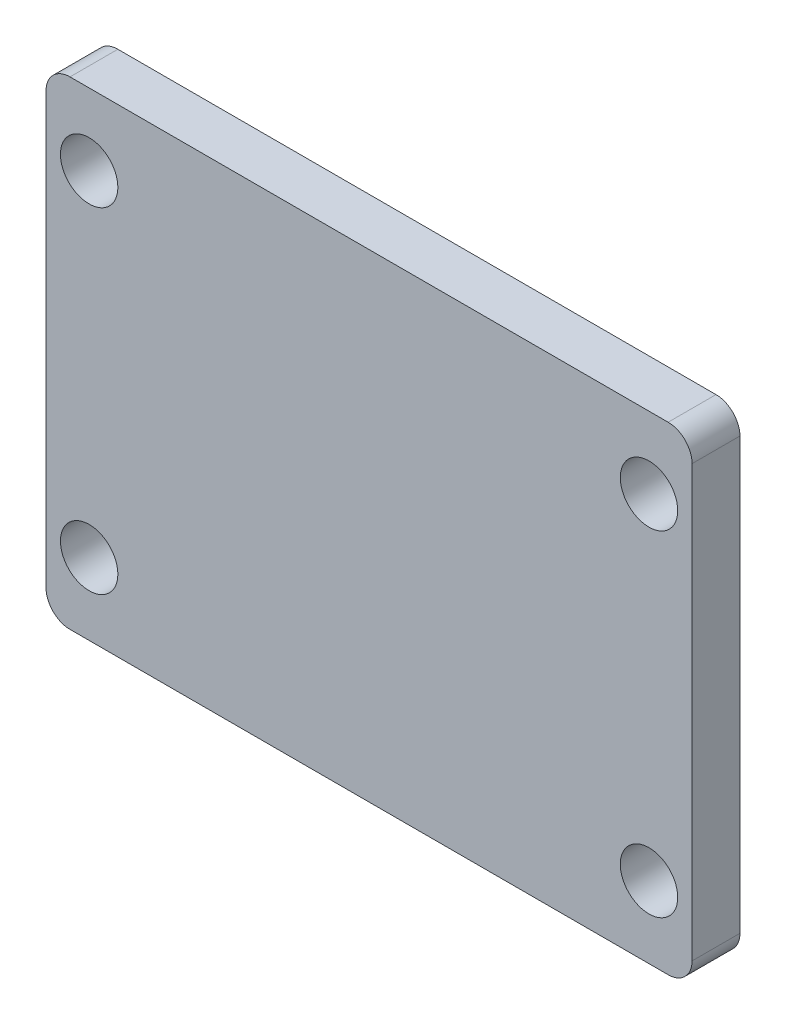
SolidWorks part; units mm, degrees
ref_plane "Front Plane" through (0, 0, 0) normal (1, 0, 0) x (0, 1, 0)
ref_plane "Top Plane" through (0, 0, 0) normal (0, 0, 1) x (0, 1, 0)
ref_plane "Right Plane" through (0, 0, 0) normal (0, 1, 0) x (-1, 0, 0)
sketch "Sketch2" plane through (0, 0, 0) normal (0, 0, 1) x (0, 1, 0)
  line L1 (-45, -67.5) -> (45, -67.5)
  line L2 (-50, -62.5) -> (-50, 62.5)
  line L3 (-45, 67.5) -> (45, 67.5)
  line L4 (50, -62.5) -> (50, 62.5)
  line L5 (-50, -67.5) -> (50, 67.5) construction
  line L6 (-50, 67.5) -> (50, -67.5) construction
  circle A0 centre (-35, 58.5) radius 6
  circle A1 centre (35, 58.5) radius 6
  circle A2 centre (35, -58.5) radius 6
  circle A3 centre (-35, -58.5) radius 6
  arc A4 (-45, -67.5) -> (-50, -62.5) centre (-45, -62.5) cw
  arc A5 (45, -67.5) -> (50, -62.5) centre (45, -62.5) ccw
  arc A6 (45, 67.5) -> (50, 62.5) centre (45, 62.5) cw
  arc A7 (-50, 62.5) -> (-45, 67.5) centre (-45, 62.5) cw
  point P0 (0, 0)
  dimension "D5" = 12
  dimension "D8" = 5
  dimension "D1" = 135
  dimension "D2" = 100
  dimension "D3" = 9
  dimension "D4" = 15
  dimension "D6" = 2
  dimension "D7" = 2
extrude "Boss-Extrude1" add sketch "Sketch2" along normal blind 10
